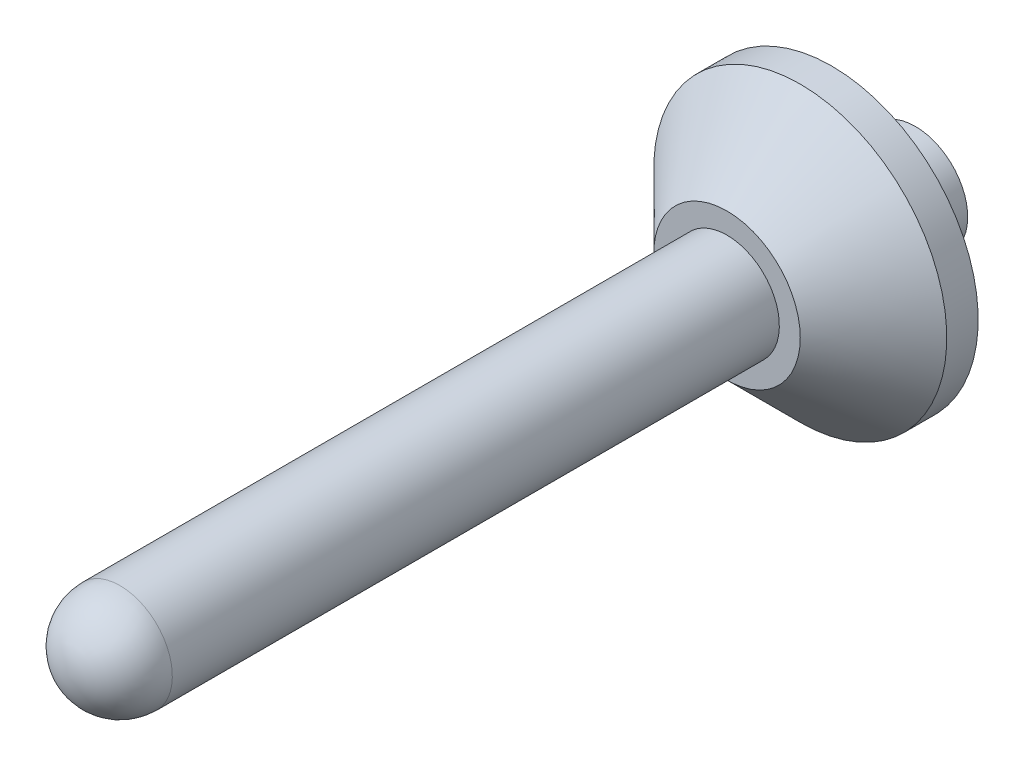
SolidWorks part; units mm, degrees
ref_plane "前视基准面" through (0, 0, 0) normal (0, 0, 1) x (1, 0, 0)
ref_plane "上视基准面" through (0, 0, 0) normal (0, 1, 0) x (1, 0, 0)
ref_plane "右视基准面" through (0, 0, 0) normal (1, 0, 0) x (0, 0, -1)
sketch "草图1" plane through (0, 0, 0) normal (1, 0, 0) x (0, 0, -1)
  line L0 (0, 0) -> (-76, 0) construction
  line L1 (-76, 5) -> (-20, 5)
  line L2 (-20, 5) -> (-11, 14)
  line L3 (-11, 14) -> (-8, 14)
  line L4 (-8, 14) -> (-8, 5)
  line L5 (-8, 5) -> (0, 5)
  line L6 (0, 5) -> (0, 0)
  line L7 (-76, 0) -> (-81, 0) construction
  line L8 (0, 0) -> (-81, 0)
  arc A0 (-76, 5) -> (-81, 0) centre (-76, 0) ccw
  point P9 (-17.4501, 5)
  point P12 (-19.9497, 5)
  point P13 (-8, 3.9488)
  point P14 (-8, 14)
  dimension "D1" = 10
  dimension "D2" = 14
  dimension "D3" = 81
  dimension "D4" = 45
  dimension "D5" = 3
  dimension "D6" = 8
  dimension "D7" = 10
revolve "旋转1" add sketch "草图1" angle 360 about L8
sketch "草图2" plane through (0, 0, 8) normal (0, 0, -1) x (-1, 0, 0)
  circle A0 centre (0, 0) radius 12
  circle A1 centre (0, 0) radius 5
  circle A2 centre (0, 0) radius 5
  dimension "D2" = 24
  dimension "D1" = 0
extrude "切除-拉伸1" cut sketch "草图2" against normal blind 3
sketch "草图3" plane through (0, 0, 0) normal (0, 1, 0) x (1, 0, 0)
  line L0 (5, -20) -> (5, -18)
  line L1 (5, -18) -> (10, -18)
  line L2 (10, -18) -> (10, -20)
  line L3 (10, -20) -> (5, -20)
  line L4 (0, -20) -> (0, -29.9085) construction
  dimension "D1" = 2
  dimension "D2" = 5
revolve "切除-旋转1" cut sketch "草图3" angle 360 about L4
